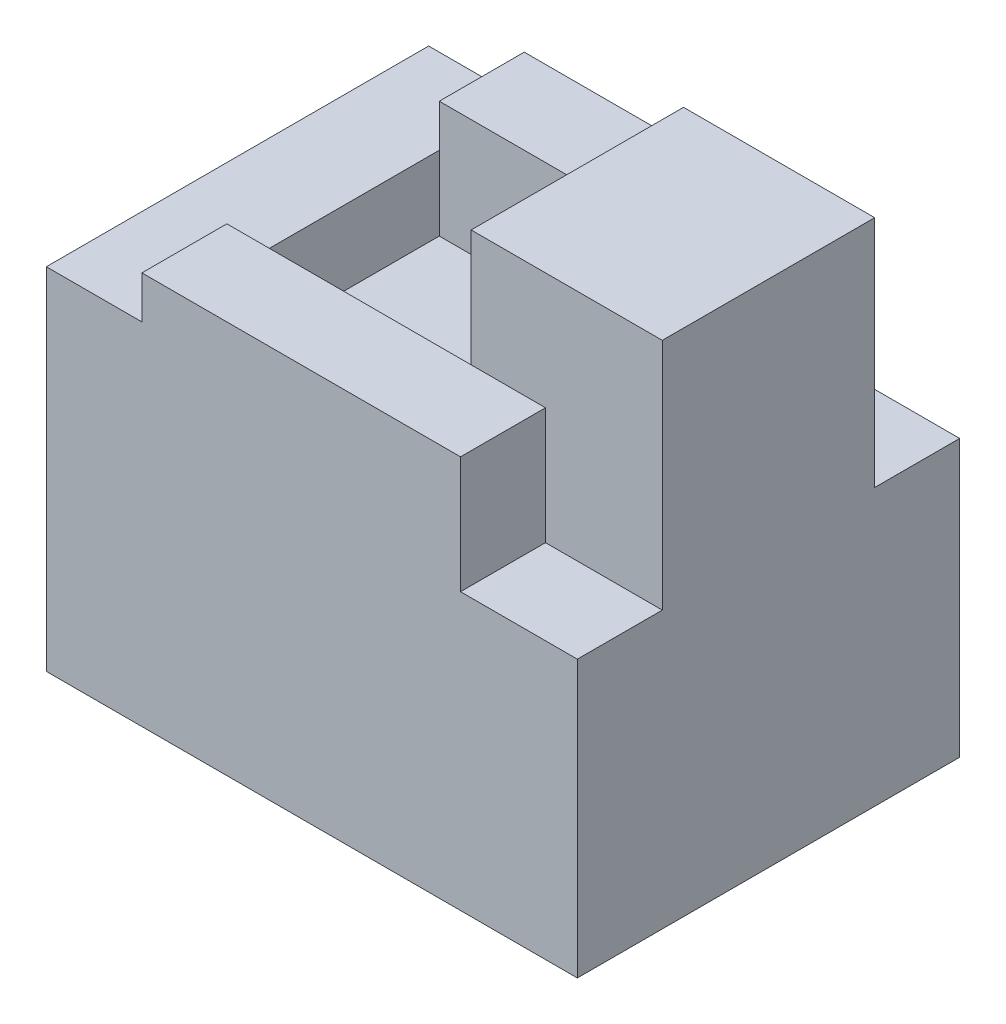
SolidWorks part; units mm, degrees
ref_plane "Front Plane" through (0, 0, 0) normal (0, 0, 1) x (1, 0, 0)
ref_plane "Top Plane" through (0, 0, 0) normal (0, 1, 0) x (1, 0, 0)
ref_plane "Right Plane" through (0, 0, 0) normal (1, 0, 0) x (0, 0, -1)
sketch "Sketch1" plane through (0, 0, 0) normal (0, 1, 0) x (1, 0, 0)
  line L1 (0, 0) -> (500, 0)
  line L2 (0, 0) -> (0, 360)
  line L3 (0, 360) -> (500, 360)
  line L4 (500, 0) -> (500, 360)
  dimension "D1" = 360
  dimension "D2" = 500
extrude "Boss-Extrude1" add sketch "Sketch1" against normal blind 260
sketch "Sketch2" plane through (0, 0, 0) normal (0, 1, 0) x (1, 0, 0)
  line L0 (0, 0) -> (500, 0) construction
  line L1 (0, 360) -> (90, 360)
  line L2 (0, 360) -> (0, 0)
  line L3 (0, 0) -> (90, 0)
  line L4 (90, 360) -> (90, 0)
  dimension "D1" = 90
extrude "Boss-Extrude3" add sketch "Sketch2" along normal blind 70
sketch "Sketch3" plane through (0, 0, 0) normal (0, 1, 0) x (1, 0, 0)
  line L0 (500, 360) -> (90, 360) construction
  line L1 (390, 360) -> (90, 360)
  line L2 (390, 360) -> (390, 280)
  line L3 (390, 280) -> (90, 280)
  line L4 (90, 360) -> (90, 280)
  line L5 (90, 0) -> (500, 0) construction
  line L6 (390, 0) -> (90, 0)
  line L7 (390, 0) -> (390, 80)
  line L8 (390, 80) -> (90, 80)
  line L9 (90, 0) -> (90, 80)
  line L10 (90, 0) -> (90, 360) construction
  dimension "D1" = 80
  dimension "D2" = 80
  dimension "D3" = 300
  dimension "D4" = 300
extrude "Boss-Extrude4" add sketch "Sketch3" along normal blind 110
sketch "Sketch4" plane through (0, 0, 0) normal (0, 1, 0) x (1, 0, 0)
  line L0 (500, 0) -> (500, 360) construction
  line L1 (500, 280) -> (320, 280)
  line L2 (500, 280) -> (500, 80)
  line L3 (500, 80) -> (320, 80)
  line L4 (320, 280) -> (320, 80)
  point P6 (500, 180)
  dimension "D1" = 200
  dimension "D2" = 180
extrude "Boss-Extrude5" add sketch "Sketch4" along normal blind 220
